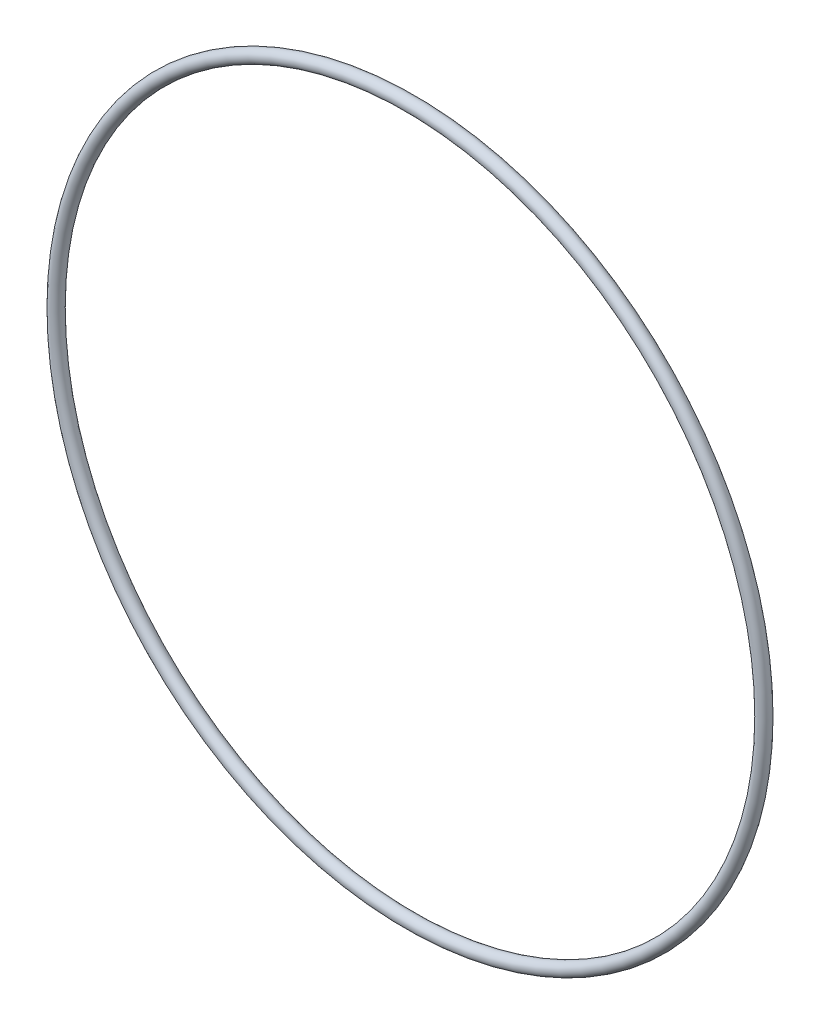
SolidWorks part; units mm, degrees
material "Copper"
ref_plane "Front Plane" through (0, 0, 0) normal (0, 0, 1) x (1, 0, 0)
ref_plane "Top Plane" through (0, 0, 0) normal (0, 1, 0) x (1, 0, 0)
ref_plane "Right Plane" through (0, 0, 0) normal (1, 0, 0) x (0, 0, -1)
sketch "Sketch1" plane through (0, 0, 0) normal (0, 0, 1) x (1, 0, 0)
  circle A0 centre (0, 0) radius 44.5
  dimension "D1" = 89
sketch "Sketch2" plane through (0, 0, 0) normal (0, 1, 0) x (1, 0, 0)
  line L0 (-44.5, 0) -> (44.5, 0) construction
  circle A0 centre (44.5, 0) radius 1
  dimension "D1" = 2
sweep "Sweep1" add path "Sketch1" circular profile diameter 1.6256 parameters "D3"=1.6256
